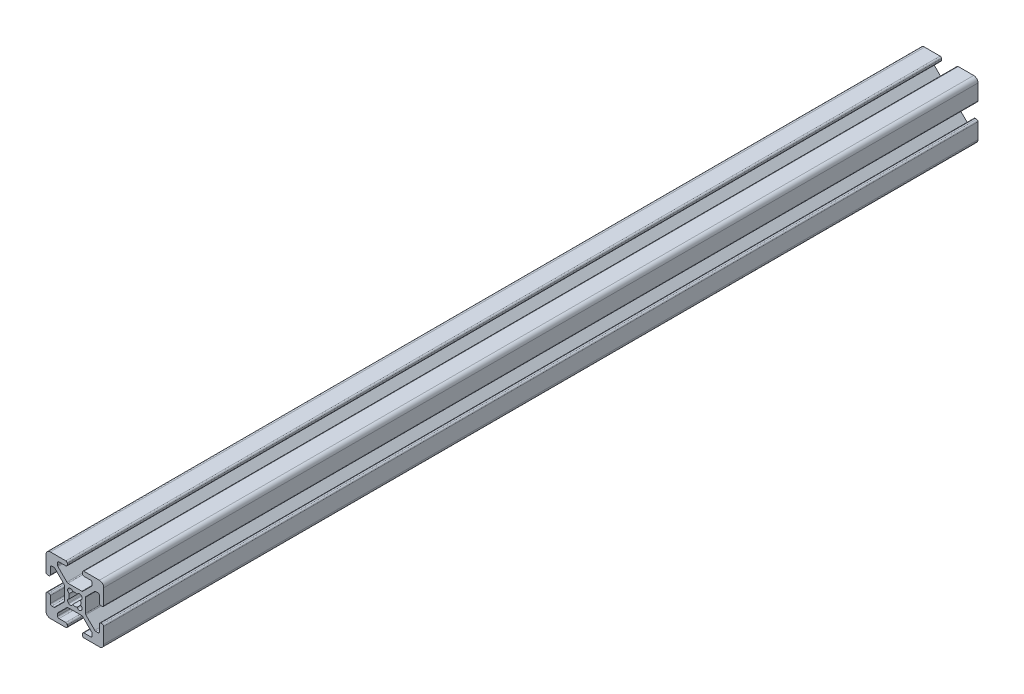
SolidWorks part; units mm, degrees
ref_plane "Front Plane" through (0, 0, 0) normal (0, 0, 1) x (1, 0, 0)
ref_plane "Top Plane" through (0, 0, 0) normal (0, 1, 0) x (1, 0, 0)
ref_plane "Right Plane" through (0, 0, 0) normal (1, 0, 0) x (0, 0, -1)
sketch "Sketch1" plane through (0, 0, 0) normal (0, 0, 1) x (1, 0, 0)
  line L0 (-5.0323, -0.3411) -> (-5.5163, -0.3411)
  line L1 (-6.0243, 0.1669) -> (-6.0243, 2.5159)
  line L2 (-4.5243, 0.1669) -> (-4.5243, 5.5289)
  line L3 (-10.8693, -5.355) -> (-10.8693, -0.5871)
  line L4 (-7.2582, 3.0239) -> (-6.5323, 3.0239)
  line L5 (-7.6174, 2.8752) -> (-10.7205, -0.2279)
  line L6 (-5.0323, -5.6011) -> (-5.5163, -5.6011)
  line L7 (-4.5243, -6.1091) -> (-4.5243, -11.4711)
  line L8 (-6.0243, -6.1091) -> (-6.0243, -8.4581)
  line L9 (-7.2582, -8.9661) -> (-6.5323, -8.9661)
  line L10 (-7.6174, -8.8173) -> (-10.7205, -5.7142)
  line L11 (-12.3994, -5.2756) -> (-12.2198, -5.096)
  line L12 (-17.1543, 6.5209) -> (-17.1543, 6.0369)
  line L13 (-17.6623, 7.0289) -> (-23.0243, 7.0289)
  line L14 (-17.6623, 5.5289) -> (-20.0113, 5.5289)
  line L15 (-12.1404, 0.6839) -> (-16.9082, 0.6839)
  line L16 (-20.5193, 4.295) -> (-20.5193, 5.0209)
  line L17 (-20.3705, 3.9358) -> (-17.2674, 0.8327)
  line L18 (-11.8943, 6.5209) -> (-11.8943, 6.0369)
  line L19 (-11.3863, 7.0289) -> (-6.0243, 7.0289)
  line L20 (-11.3863, 5.5289) -> (-9.0373, 5.5289)
  line L21 (-8.5293, 4.295) -> (-8.5293, 5.0209)
  line L22 (-8.6781, 3.9358) -> (-11.7812, 0.8327)
  line L23 (-12.2198, -0.8462) -> (-12.3994, -0.6666)
  line L24 (-24.0163, -5.6011) -> (-23.5323, -5.6011)
  line L25 (-24.5243, -6.1091) -> (-24.5243, -11.4711)
  line L26 (-23.0243, -6.1091) -> (-23.0243, -8.4581)
  line L27 (-18.1793, -0.5871) -> (-18.1793, -5.355)
  line L28 (-21.7904, -8.9661) -> (-22.5163, -8.9661)
  line L29 (-21.4312, -8.8173) -> (-18.3281, -5.7142)
  line L30 (-24.0163, -0.3411) -> (-23.5323, -0.3411)
  line L31 (-24.5243, 0.1669) -> (-24.5243, 5.5289)
  line L32 (-23.0243, 0.1669) -> (-23.0243, 2.5159)
  line L33 (-21.7904, 3.0239) -> (-22.5163, 3.0239)
  line L34 (-21.4312, 2.8752) -> (-18.3281, -0.2279)
  line L35 (-16.6492, -0.6666) -> (-16.8288, -0.8462)
  line L36 (-11.8943, -12.4631) -> (-11.8943, -11.9791)
  line L37 (-11.3863, -12.9711) -> (-6.0243, -12.9711)
  line L38 (-11.3863, -11.4711) -> (-9.0373, -11.4711)
  line L39 (-16.9082, -6.6261) -> (-12.1404, -6.6261)
  line L40 (-8.5293, -10.2371) -> (-8.5293, -10.9631)
  line L41 (-8.6781, -9.8779) -> (-11.7812, -6.7748)
  line L42 (-17.1543, -12.4631) -> (-17.1543, -11.9791)
  line L43 (-17.6623, -12.9711) -> (-23.0243, -12.9711)
  line L44 (-17.6623, -11.4711) -> (-20.0113, -11.4711)
  line L45 (-20.5193, -10.2371) -> (-20.5193, -10.9631)
  line L46 (-20.3705, -9.8779) -> (-17.2674, -6.7748)
  line L47 (-16.8288, -5.096) -> (-16.6492, -5.2756)
  arc A0 (-15.3283, -4.9062) -> (-13.7203, -4.9062) centre (-14.5243, -2.9711) ccw
  arc A1 (-6.0243, 2.5159) -> (-6.5323, 3.0239) centre (-6.5323, 2.5159) ccw
  arc A2 (-7.2582, 3.0239) -> (-7.6174, 2.8752) centre (-7.2582, 2.5159) ccw
  arc A3 (-10.7205, -0.2279) -> (-10.8693, -0.5871) centre (-10.3613, -0.5871) ccw
  arc A4 (-10.8693, -5.355) -> (-10.7205, -5.7142) centre (-10.3613, -5.355) ccw
  arc A5 (-7.6174, -8.8173) -> (-7.2582, -8.9661) centre (-7.2582, -8.4581) ccw
  arc A6 (-6.5323, -8.9661) -> (-6.0243, -8.4581) centre (-6.5323, -8.4581) ccw
  arc A7 (-5.5163, -5.6011) -> (-6.0243, -6.1091) centre (-5.5163, -6.1091) ccw
  arc A8 (-4.5243, -6.1091) -> (-5.0323, -5.6011) centre (-5.0323, -6.1091) ccw
  arc A9 (-5.0323, -0.3411) -> (-4.5243, 0.1669) centre (-5.0323, 0.1669) ccw
  arc A10 (-6.0243, 0.1669) -> (-5.5163, -0.3411) centre (-5.5163, 0.1669) ccw
  arc A11 (-13.7203, -4.9062) -> (-12.3994, -5.2756) centre (-12.9559, -4.7191) ccw
  arc A12 (-12.2198, -5.096) -> (-12.5892, -3.775) centre (-12.7763, -4.5395) ccw
  arc A13 (-17.1543, 6.5209) -> (-17.6623, 7.0289) centre (-17.6623, 6.5209) ccw
  arc A14 (-17.6623, 5.5289) -> (-17.1543, 6.0369) centre (-17.6623, 6.0369) ccw
  arc A15 (-12.5892, -3.775) -> (-12.5892, -2.1671) centre (-14.5243, -2.9711) ccw
  arc A16 (-17.2674, 0.8327) -> (-16.9082, 0.6839) centre (-16.9082, 1.1919) ccw
  arc A17 (-20.0113, 5.5289) -> (-20.5193, 5.0209) centre (-20.0113, 5.0209) ccw
  arc A18 (-20.5193, 4.295) -> (-20.3705, 3.9358) centre (-20.0113, 4.295) ccw
  arc A19 (-11.8943, 6.0369) -> (-11.3863, 5.5289) centre (-11.3863, 6.0369) ccw
  arc A20 (-11.3863, 7.0289) -> (-11.8943, 6.5209) centre (-11.3863, 6.5209) ccw
  arc A21 (-8.5293, 5.0209) -> (-9.0373, 5.5289) centre (-9.0373, 5.0209) ccw
  arc A22 (-8.6781, 3.9358) -> (-8.5293, 4.295) centre (-9.0373, 4.295) ccw
  arc A23 (-12.1404, 0.6839) -> (-11.7812, 0.8327) centre (-12.1404, 1.1919) ccw
  arc A24 (-12.5892, -2.1671) -> (-12.2198, -0.8462) centre (-12.7763, -1.4027) ccw
  arc A25 (-12.3994, -0.6666) -> (-13.7203, -1.0359) centre (-12.9559, -1.223) ccw
  arc A26 (-24.0163, -5.6011) -> (-24.5243, -6.1091) centre (-24.0163, -6.1091) ccw
  arc A27 (-23.0243, -6.1091) -> (-23.5323, -5.6011) centre (-23.5323, -6.1091) ccw
  arc A28 (-13.7203, -1.0359) -> (-15.3283, -1.0359) centre (-14.5243, -2.9711) ccw
  arc A29 (-18.3281, -5.7142) -> (-18.1793, -5.355) centre (-18.6873, -5.355) ccw
  arc A30 (-23.0243, -8.4581) -> (-22.5163, -8.9661) centre (-22.5163, -8.4581) ccw
  arc A31 (-21.7904, -8.9661) -> (-21.4312, -8.8173) centre (-21.7904, -8.4581) ccw
  arc A32 (-23.5323, -0.3411) -> (-23.0243, 0.1669) centre (-23.5323, 0.1669) ccw
  arc A33 (-24.5243, 0.1669) -> (-24.0163, -0.3411) centre (-24.0163, 0.1669) ccw
  arc A34 (-22.5163, 3.0239) -> (-23.0243, 2.5159) centre (-22.5163, 2.5159) ccw
  arc A35 (-21.4312, 2.8752) -> (-21.7904, 3.0239) centre (-21.7904, 2.5159) ccw
  arc A36 (-18.1793, -0.5871) -> (-18.3281, -0.2279) centre (-18.6873, -0.5871) ccw
  arc A37 (-15.3283, -1.0359) -> (-16.6492, -0.6666) centre (-16.0927, -1.223) ccw
  arc A38 (-16.8288, -0.8462) -> (-16.4594, -2.1671) centre (-16.2723, -1.4027) ccw
  arc A39 (-11.8943, -12.4631) -> (-11.3863, -12.9711) centre (-11.3863, -12.4631) ccw
  arc A40 (-11.3863, -11.4711) -> (-11.8943, -11.9791) centre (-11.3863, -11.9791) ccw
  arc A41 (-16.4594, -2.1671) -> (-16.4594, -3.775) centre (-14.5243, -2.9711) ccw
  arc A42 (-11.7812, -6.7748) -> (-12.1404, -6.6261) centre (-12.1404, -7.1341) ccw
  arc A43 (-9.0373, -11.4711) -> (-8.5293, -10.9631) centre (-9.0373, -10.9631) ccw
  arc A44 (-8.5293, -10.2371) -> (-8.6781, -9.8779) centre (-9.0373, -10.2371) ccw
  arc A45 (-17.1543, -11.9791) -> (-17.6623, -11.4711) centre (-17.6623, -11.9791) ccw
  arc A46 (-17.6623, -12.9711) -> (-17.1543, -12.4631) centre (-17.6623, -12.4631) ccw
  arc A47 (-20.5193, -10.9631) -> (-20.0113, -11.4711) centre (-20.0113, -10.9631) ccw
  arc A48 (-20.3705, -9.8779) -> (-20.5193, -10.2371) centre (-20.0113, -10.2371) ccw
  arc A49 (-16.9082, -6.6261) -> (-17.2674, -6.7748) centre (-16.9082, -7.1341) ccw
  arc A50 (-16.4594, -3.775) -> (-16.8288, -5.096) centre (-16.2723, -4.5395) ccw
  arc A51 (-16.6492, -5.2756) -> (-15.3283, -4.9062) centre (-16.0927, -4.7191) ccw
  arc A52 (-4.5243, 5.5289) -> (-6.0243, 7.0289) centre (-6.0243, 5.5289) ccw
  arc A53 (-6.0243, -12.9711) -> (-4.5243, -11.4711) centre (-6.0243, -11.4711) ccw
  arc A54 (-24.5243, -11.4711) -> (-23.0243, -12.9711) centre (-23.0243, -11.4711) ccw
  arc A55 (-23.0243, 7.0289) -> (-24.5243, 5.5289) centre (-23.0243, 5.5289) ccw
extrude "Extrude1" add sketch "Sketch1" along normal blind 303
